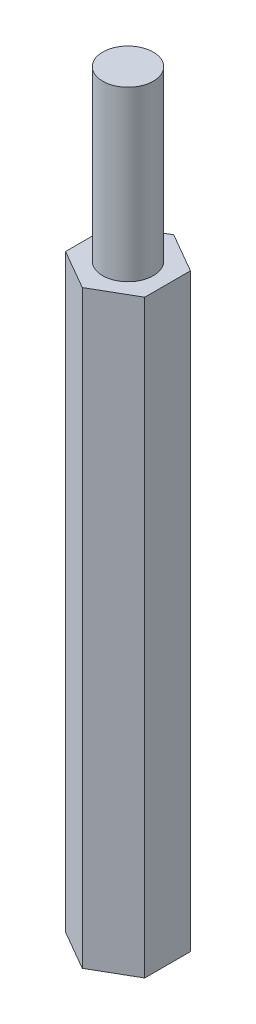
SolidWorks part; units mm, degrees
ref_plane "Front Plane" through (0, 0, 0) normal (0, 0, 1) x (1, 0, 0)
ref_plane "Top Plane" through (0, 0, 0) normal (0, 1, 0) x (1, 0, 0)
ref_plane "Right Plane" through (0, 0, 0) normal (1, 0, 0) x (0, 0, -1)
sketch "Sketch1" plane through (0, 0, 0) normal (0, 1, 0) x (1, 0, 0)
  line L1 (0, 2.7135) -> (-2.35, 1.3568)
  line L2 (-2.35, 1.3568) -> (-2.35, -1.3568)
  line L3 (-2.35, -1.3568) -> (0, -2.7135)
  line L4 (0, -2.7135) -> (2.35, -1.3568)
  line L5 (2.35, -1.3568) -> (2.35, 1.3568)
  line L6 (2.35, 1.3568) -> (0, 2.7135)
  circle A0 centre (0, 0) radius 2.35 construction
  dimension "D1" = 4.7
extrude "Boss-Extrude1" add sketch "Sketch1" along normal blind 35
sketch "Sketch2" plane through (0, 35, 0) normal (0, 1, 0) x (1, 0, 0)
  circle A0 centre (0, 0) radius 1.5
  dimension "D1" = 3
extrude "Boss-Extrude2" add sketch "Sketch2" along normal blind 10
sketch "Sketch5" plane through (0, 0, 0) normal (0, -1, 0) x (1, 0, 0)
  circle A0 centre (0, 0) radius 1.5
  dimension "D1" = 3
extrude "Cut-Extrude1" cut sketch "Sketch5" against normal blind 10
